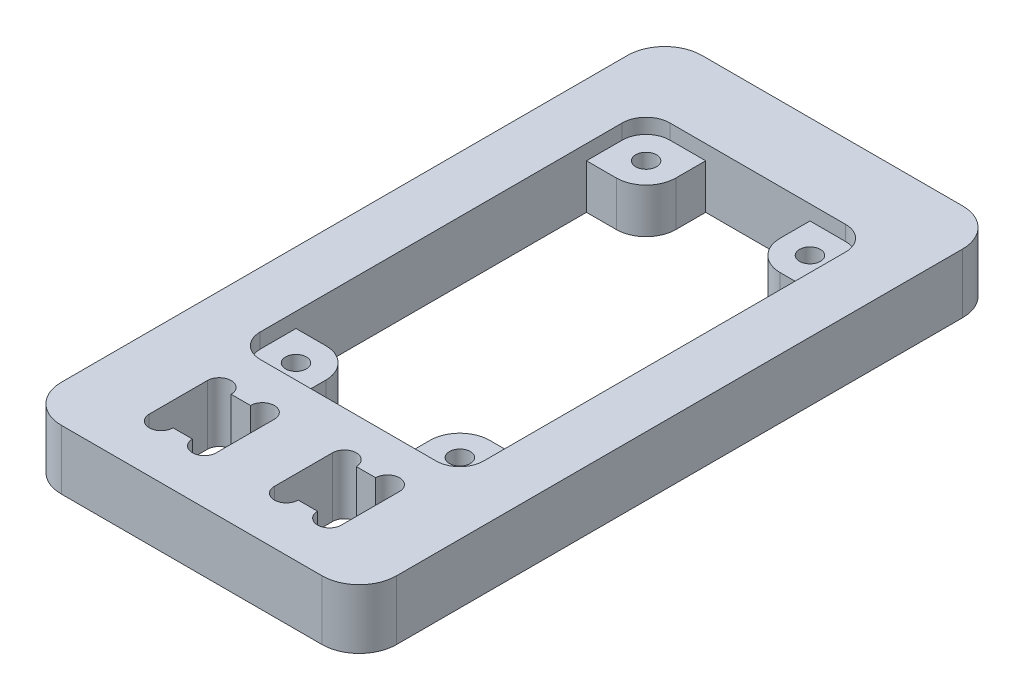
SolidWorks part; units mm, degrees
ref_plane "Front Plane" through (0, 0, 0) normal (0, 0, 1) x (1, 0, 0)
ref_plane "Top Plane" through (0, 0, 0) normal (0, 1, 0) x (1, 0, 0)
ref_plane "Right Plane" through (0, 0, 0) normal (1, 0, 0) x (0, 0, -1)
sketch "Sketch1" plane through (0, 0, 0) normal (0, 1, 0) x (1, 0, 0)
  line L0 (-15, 36) -> (-15, -40)
  line L1 (-10, -45) -> (25, -45)
  line L2 (30, 36) -> (30, -40)
  line L3 (-10, 41) -> (25, 41)
  line L4 (-2.2, -37.8) -> (0.4, -37.8)
  line L5 (-5.4, -30) -> (-5.4, -37.8)
  line L6 (-2.2, -30) -> (0.4, -30)
  line L7 (3.6, -30) -> (3.6, -37.8)
  line L8 (14.6, -37.8) -> (17.2, -37.8)
  line L9 (11.4, -30) -> (11.4, -37.8)
  line L10 (14.6, -30) -> (17.2, -30)
  line L11 (20.4, -30) -> (20.4, -37.8)
  line L12 (18.5, -16) -> (22.5, -16)
  line L13 (14.5, -20) -> (14.5, -24)
  line L14 (0.5, -24) -> (14.5, -24)
  line L15 (0.5, -20) -> (0.5, -24)
  line L16 (-3.5, -16) -> (-7.5, -16)
  line L17 (-7.5, 23) -> (-7.5, -16)
  line L18 (-3.5, 23) -> (-7.5, 23)
  line L19 (0.5, 27) -> (0.5, 31)
  line L20 (0.5, 31) -> (14.5, 31)
  line L21 (14.5, 27) -> (14.5, 31)
  line L22 (18.5, 23) -> (22.5, 23)
  line L23 (22.5, 23) -> (22.5, -16)
  circle A0 centre (18.5, -20) radius 1.4
  circle A1 centre (-3.5, -20) radius 1.4
  circle A2 centre (18.5, 27) radius 1.4
  circle A3 centre (-3.5, 27) radius 1.4
  arc A4 (-10, 41) -> (-15, 36) centre (-10, 36) ccw
  arc A5 (-15, -40) -> (-10, -45) centre (-10, -40) ccw
  arc A6 (25, -45) -> (30, -40) centre (25, -40) ccw
  arc A7 (30, 36) -> (25, 41) centre (25, 36) ccw
  arc A8 (0.4, -37.8) -> (3.6, -37.8) centre (2, -37.8) ccw
  arc A9 (-5.4, -37.8) -> (-2.2, -37.8) centre (-3.8, -37.8) ccw
  arc A10 (-2.2, -30) -> (-5.4, -30) centre (-3.8, -30) ccw
  arc A11 (3.6, -30) -> (0.4, -30) centre (2, -30) ccw
  arc A12 (17.2, -37.8) -> (20.4, -37.8) centre (18.8, -37.8) ccw
  arc A13 (11.4, -37.8) -> (14.6, -37.8) centre (13, -37.8) ccw
  arc A14 (14.6, -30) -> (11.4, -30) centre (13, -30) ccw
  arc A15 (20.4, -30) -> (17.2, -30) centre (18.8, -30) ccw
  arc A16 (18.5, -16) -> (14.5, -20) centre (18.5, -20) ccw
  arc A17 (0.5, -20) -> (-3.5, -16) centre (-3.5, -20) ccw
  arc A18 (-3.5, 23) -> (0.5, 27) centre (-3.5, 27) ccw
  arc A19 (14.5, 27) -> (18.5, 23) centre (18.5, 27) ccw
extrude "Boss-Extrude1" add sketch "Sketch1" along normal blind 8
sketch "Sketch2" plane through (0, 8, 0) normal (0, 1, 0) x (1, 0, 0)
  line L0 (14.5, 31) -> (0.5, 31) construction
  line L1 (-4.3, 31) -> (19.3, 31)
  line L2 (-7.5, 27.8) -> (-7.5, -20.8)
  line L3 (-4.3, -24) -> (19.3, -24)
  line L4 (22.5, 27.8) -> (22.5, -20.8)
  line L5 (-7.5, 23) -> (-7.5, -16) construction
  line L6 (22.5, -16) -> (22.5, 23) construction
  line L7 (0.5, -24) -> (14.5, -24) construction
  arc A0 (22.5, -20.8) -> (19.3, -24) centre (19.3, -20.8) cw
  arc A1 (-7.5, -20.8) -> (-4.3, -24) centre (-4.3, -20.8) ccw
  arc A2 (-7.5, 27.8) -> (-4.3, 31) centre (-4.3, 27.8) cw
  arc A3 (19.3, 31) -> (22.5, 27.8) centre (19.3, 27.8) cw
  dimension "D1" = 3.2
extrude "Cut-Extrude1" cut sketch "Sketch2" against normal blind 2 contours A2 L1 A3 L4 A0 L3 A1 L2
